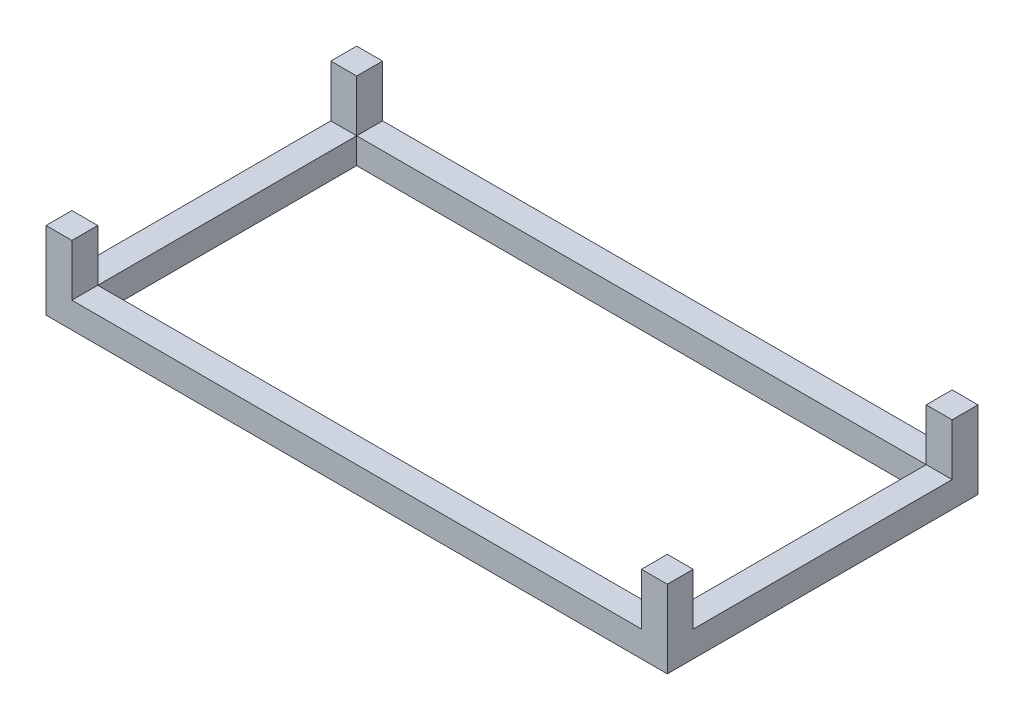
SolidWorks part; units mm, degrees
ref_plane "Front Plane" through (0, 0, 0) normal (0, 0, 1) x (1, 0, 0)
ref_plane "Top Plane" through (0, 0, 0) normal (0, 1, 0) x (1, 0, 0)
ref_plane "Right Plane" through (0, 0, 0) normal (1, 0, 0) x (0, 0, -1)
sketch "Sketch2" plane through (0, 0, 0) normal (0, 1, 0) x (1, 0, 0)
  line L1 (-76.2, 38.1) -> (76.2, 38.1)
  line L2 (-76.2, 38.1) -> (-76.2, -38.1)
  line L3 (-76.2, -38.1) -> (76.2, -38.1)
  line L4 (76.2, 38.1) -> (76.2, -38.1)
  point P4 (0, 0)
  point P5 (0, 0)
extrude "Boss-Extrude2" add sketch "Sketch2" against normal blind 6.35
sketch "Sketch3" plane through (0, -6.35, 0) normal (0, -1, 0) x (-1, 0, 0)
  line L1 (69.85, -31.75) -> (-69.85, -31.75)
  line L2 (69.85, -31.75) -> (69.85, 31.75)
  line L3 (69.85, 31.75) -> (-69.85, 31.75)
  line L4 (-69.85, -31.75) -> (-69.85, 31.75)
  point P4 (0, 0)
  point P5 (0, 0)
  point P6 (0, 0)
extrude "Cut-Extrude1" cut sketch "Sketch3" against normal blind 6.35
sketch "Sketch4" plane through (0, 0, 0) normal (0, 1, 0) x (1, 0, 0)
  line L1 (-76.2, 38.1) -> (-69.85, 38.1)
  line L2 (-76.2, 38.1) -> (-76.2, 31.75)
  line L3 (-76.2, 31.75) -> (-69.85, 31.75)
  line L4 (-69.85, 38.1) -> (-69.85, 31.75)
  line L5 (-69.85, -31.75) -> (-76.2, -31.75)
  line L6 (-69.85, -31.75) -> (-69.85, -38.1)
  line L7 (-69.85, -38.1) -> (-76.2, -38.1)
  line L8 (-76.2, -31.75) -> (-76.2, -38.1)
  line L9 (69.85, -31.75) -> (76.2, -31.75)
  line L10 (69.85, -31.75) -> (69.85, -38.1)
  line L11 (69.85, -38.1) -> (76.2, -38.1)
  line L12 (76.2, -31.75) -> (76.2, -38.1)
  line L13 (69.85, 31.75) -> (76.2, 31.75)
  line L14 (69.85, 31.75) -> (69.85, 38.1)
  line L15 (69.85, 38.1) -> (76.2, 38.1)
  line L16 (76.2, 31.75) -> (76.2, 38.1)
  point P24 (0, 0)
  point P25 (0, 0)
  point P26 (-57.15, -31.75)
extrude "Boss-Extrude3" add sketch "Sketch4" along normal blind 12.7
